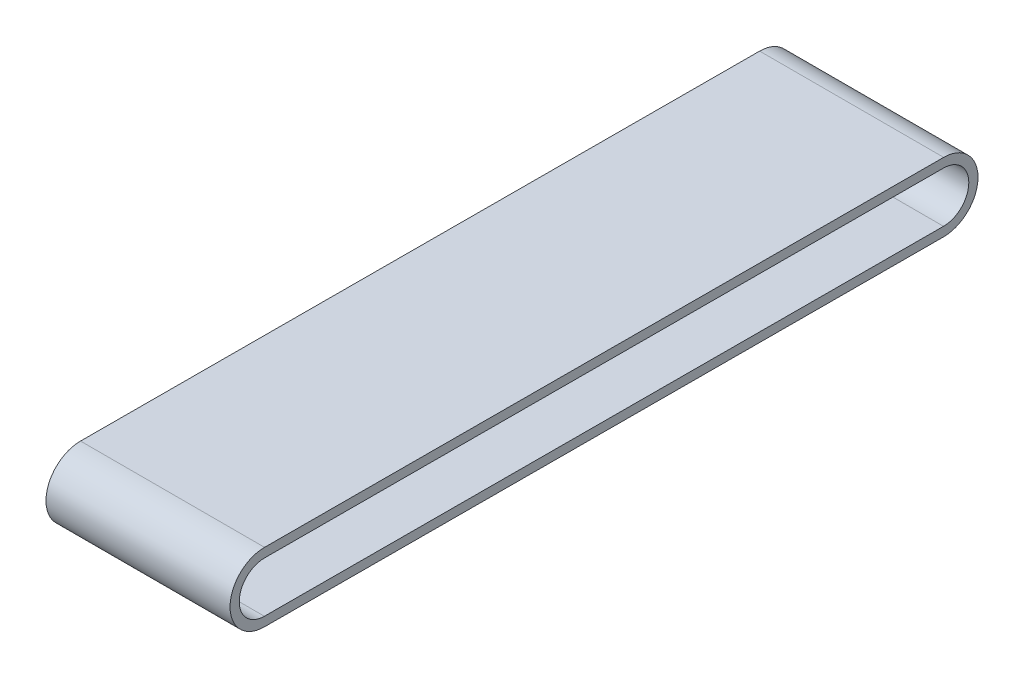
SolidWorks part; units mm, degrees
material "NEOPRENE"
ref_plane "Front Plane" through (0, 0, 0) normal (0, 0, 1) x (1, 0, 0)
ref_plane "Top Plane" through (0, 0, 0) normal (0, 1, 0) x (1, 0, 0)
ref_plane "Right Plane" through (0, 0, 0) normal (1, 0, 0) x (0, 0, -1)
sketch "Sketch1" plane through (0, 0, 0) normal (1, 0, 0) x (0, 0, -1)
  line L4 (364.4385, 62.2815) -> (739.3425, 61.2655)
  line L5 (739.4455, 99.2625) -> (364.5415, 100.2785)
  line L6 (364.4385, 62.2815) -> (739.3425, 61.2655)
  line L7 (739.4455, 99.2625) -> (364.5415, 100.2785)
  arc A6 (364.5415, 100.2785) -> (364.4385, 62.2815) centre (364.49, 81.28) ccw
  arc A7 (739.3425, 61.2655) -> (739.4455, 99.2625) centre (739.394, 80.264) ccw
  arc A10 (364.5415, 100.2785) -> (364.4385, 62.2815) centre (364.49, 81.28) ccw
  arc A11 (739.3425, 61.2655) -> (739.4455, 99.2625) centre (739.394, 80.264) ccw
  dimension "D2" = 0
extrude "Extrude-Thin1" add sketch "Sketch1" along normal mid plane 101.6 thin thin type one direction reverse wall 5.08
